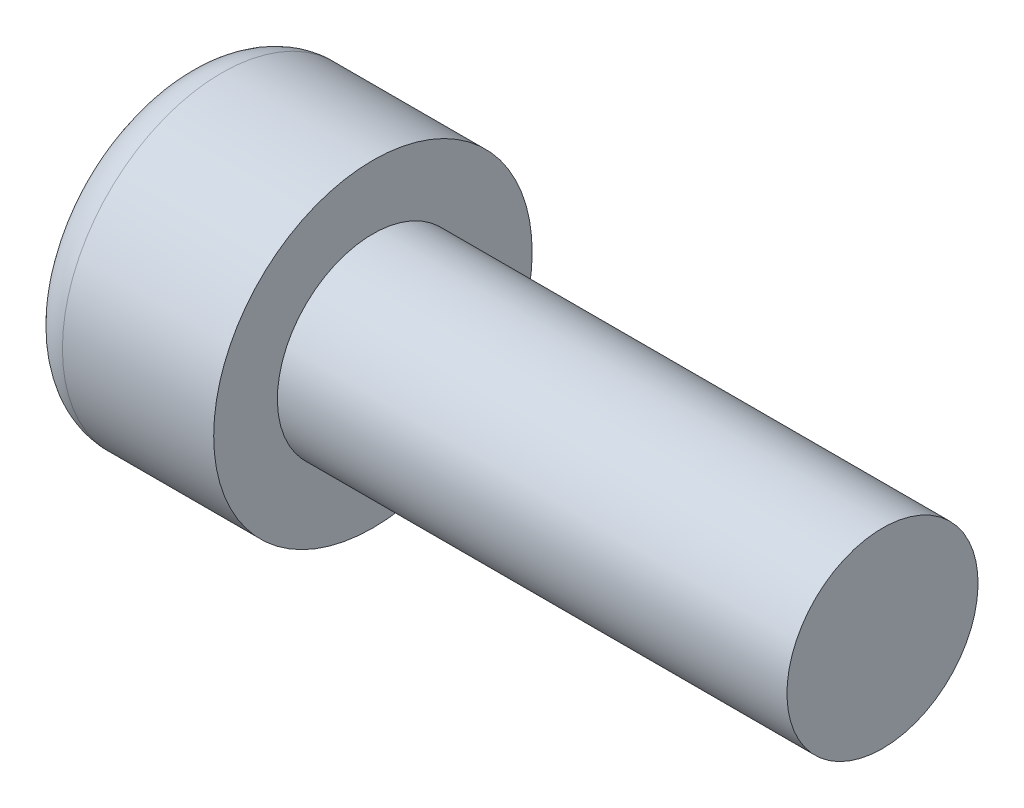
SolidWorks part; units mm, degrees
material "Plain Carbon Steel"
ref_plane "Front Plane" through (0, 0, 0) normal (0, 0, 1) x (1, 0, 0)
ref_plane "Top Plane" through (0, 0, 0) normal (0, 1, 0) x (1, 0, 0)
ref_plane "Right Plane" through (0, 0, 0) normal (1, 0, 0) x (0, 0, -1)
sketch "Sketch1" plane through (0, 0, 0) normal (0, 0, 1) x (1, 0, 0)
  line L0 (0, 0) -> (0, 3.75)
  line L1 (1.25, 5) -> (6, 5)
  line L2 (6, 5) -> (6, 3)
  line L3 (6, 3) -> (22, 3)
  line L4 (22, 3) -> (22, 0)
  line L5 (22, 0) -> (0, 0) construction
  line L6 (1.25, 3.75) -> (1.25, 2.5) construction
  line L7 (1.25, 2.5) -> (1.25, 1.25) construction
  line L8 (1.25, 1.25) -> (1.25, 0) construction
  line L9 (1.25, 5) -> (1.25, 3.75) construction
  line L10 (0, 0) -> (22, 0)
  arc A0 (0, 3.75) -> (1.25, 5) centre (1.25, 3.75) cw
  dimension "D1" = 6
  dimension "D2" = 10
  dimension "D3" = 6
  dimension "D4" = 16
revolve "Revolve1" add sketch "Sketch1" angle 360 about L10
sketch "Sketch2" plane through (0, 0, 0) normal (-1, 0, 0) x (0, 0, 1)
  line L1 (0, 2.8868) -> (-2.5, 1.4434)
  line L2 (-2.5, 1.4434) -> (-2.5, -1.4434)
  line L3 (-2.5, -1.4434) -> (0, -2.8868)
  line L4 (0, -2.8868) -> (2.5, -1.4434)
  line L5 (2.5, -1.4434) -> (2.5, 1.4434)
  line L6 (2.5, 1.4434) -> (0, 2.8868)
  circle A0 centre (0, 0) radius 2.5 construction
  dimension "D1" = 5
extrude "Cut-Extrude1" cut sketch "Sketch2" against normal blind 3.5
